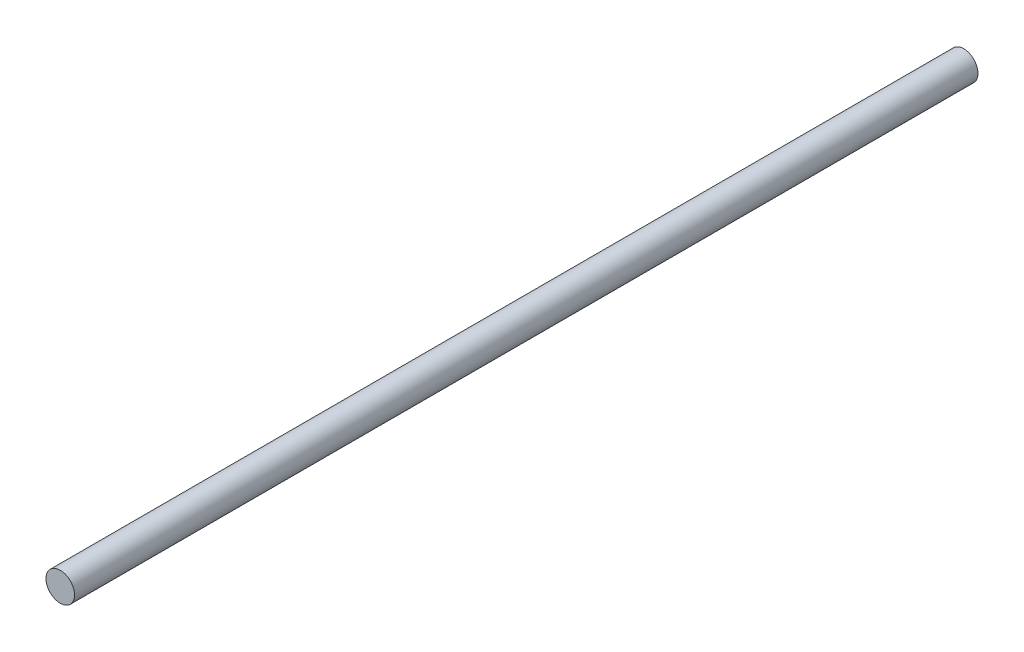
SolidWorks part; units mm, degrees
ref_plane "Спереди" through (0, 0, 0) normal (0, 0, 1) x (1, 0, 0)
ref_plane "Сверху" through (0, 0, 0) normal (0, 1, 0) x (1, 0, 0)
ref_plane "Справа" through (0, 0, 0) normal (1, 0, 0) x (0, 0, -1)
sketch "Эскиз1" plane through (0, 0, 0) normal (0, 0, 1) x (1, 0, 0)
  circle A0 centre (0, 0) radius 2.5
extrude "Вытянуть1" add sketch "Эскиз1" along normal blind 158
